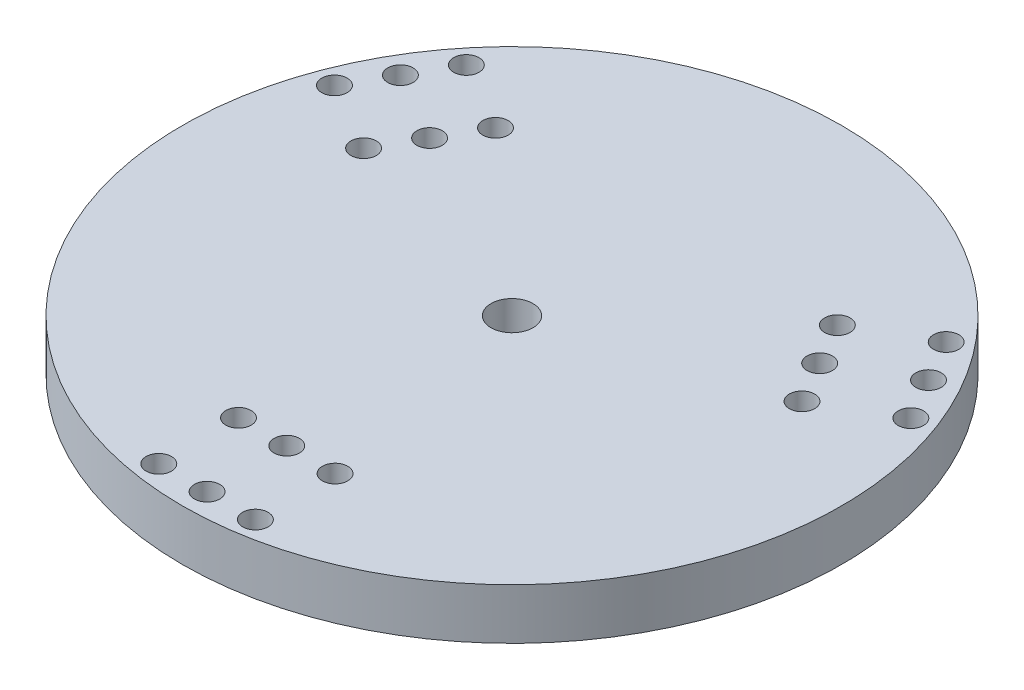
SolidWorks part; units mm, degrees
material "Carbon Fiber"
ref_plane "Front Plane" through (0, 0, 0) normal (0, 0, 1) x (1, 0, 0)
ref_plane "Top Plane" through (0, 0, 0) normal (0, 1, 0) x (1, 0, 0)
ref_plane "Right Plane" through (0, 0, 0) normal (1, 0, 0) x (0, 0, -1)
ref_plane "Plane1" through (0, 75, 0) normal (0, 1, 0) x (1, 0, 0)
sketch "Sketch1" plane through (0, 0, 0) normal (0, 1, 0) x (1, 0, 0)
  line L0 (0, 0) -> (0, -67.5) construction
  line L1 (67.5, 0) -> (-67.5, 0) construction
  line L2 (-57.6208, 33.2674) -> (-48.9649, 48.2597)
  line L3 (0, 0) -> (58.4567, 33.75) construction
  line L4 (0, 0) -> (-58.4567, 33.75) construction
  line L5 (-48.9649, 48.2597) -> (-66.2766, 18.2751)
  line L6 (-55.1208, 37.5975) -> (-60.1208, 28.9372)
  line L7 (-60.1208, 28.9372) -> (-41.6363, 18.2652)
  line L8 (0, -66.5347) -> (-17.3116, -66.5347)
  line L9 (-17.3116, -66.5347) -> (17.3116, -66.5347)
  line L10 (-41.6363, 18.2652) -> (-36.6363, 26.9255)
  line L11 (-60.1208, 28.9372) -> (-60.7961, 29.3272)
  line L12 (-55.1208, 37.5975) -> (-36.6363, 26.9255)
  line L13 (-52.6208, 41.9276) -> (-53.906, 42.6697)
  line L14 (-62.6208, 24.6071) -> (-63.906, 25.3492)
  line L15 (-52.6208, 41.9276) -> (-29.8062, 28.7556) construction
  line L16 (-39.8062, 11.4351) -> (-29.8062, 28.7556) construction
  line L17 (-62.6208, 24.6071) -> (-39.8062, 11.4351) construction
  line L18 (57.6208, 33.2674) -> (66.2766, 18.2751)
  line L19 (66.2766, 18.2751) -> (48.9649, 48.2597)
  line L20 (60.1208, 28.9372) -> (55.1208, 37.5975)
  line L21 (55.1208, 37.5975) -> (36.6363, 26.9255)
  line L22 (36.6363, 26.9255) -> (41.6363, 18.2652)
  line L23 (55.1208, 37.5975) -> (55.7961, 37.9874)
  line L24 (60.1208, 28.9372) -> (41.6363, 18.2652)
  line L25 (62.6208, 24.6071) -> (63.906, 25.3492)
  line L26 (-5, -66.5347) -> (5, -66.5347)
  line L27 (5, -66.5347) -> (5, -45.1907)
  line L28 (5, -45.1907) -> (-5, -45.1907)
  line L29 (5, -66.5347) -> (5, -67.3146)
  line L30 (-5, -66.5347) -> (-5, -45.1907)
  line L32 (52.6208, 41.9276) -> (53.906, 42.6697)
  line L33 (62.6208, 24.6071) -> (39.8062, 11.4351) construction
  line L34 (29.8062, 28.7556) -> (39.8062, 11.4351) construction
  line L35 (52.6208, 41.9276) -> (29.8062, 28.7556) construction
  line L58 (-10, -66.5347) -> (-10, -40.1907) construction
  line L59 (10, -40.1907) -> (-10, -40.1907) construction
  line L60 (10, -66.5347) -> (10, -40.1907) construction
  line L61 (-10, -66.5347) -> (-10, -68.0188)
  line L62 (10, -66.5347) -> (10, -68.0188)
  line L63 (10, -66.5347) -> (10, -67.3146) construction
  circle A0 centre (0, 0) radius 67.5
  circle A1 centre (0, 0) radius 68.75
  circle A2 centre (0, 0) radius 69.5
  circle A4 centre (0, 0) radius 5.08
  circle A5 centre (0, 0) radius 11.1125
  point P14 (0, 0)
  point P26 (-39.1363, 22.5954)
  point P39 (0, -45.1907)
  point P51 (39.1363, 22.5954)
  point P58 (0, 0)
  point P67 (0, 0)
  point P68 (0, 0)
  point P71 (0, 0)
  point P81 (0, 0)
  dimension "D1" = 135
  dimension "D2" = 137.5
  dimension "D3" = 35
  dimension "D5" = 30
  dimension "D11" = 10.16
  dimension "D12" = 22.225
  dimension "D8" = 3
  dimension "D9" = 2
  dimension "D10" = 22.3093
  dimension "D4" = 30
  dimension "D7" = 5
  dimension "D6" = 5
sketch "Sketch16" plane through (0, 75, 0) normal (0, -1, 0) x (1, 0, 0)
  line L0 (-33.6322, -30.3872) -> (-43.1322, -13.9328)
  line L1 (-47.2115, -38.2272) -> (-56.7115, -21.7728)
  line L2 (-9.5, 60) -> (9.5, 60)
  line L3 (-9.5, 44.32) -> (9.5, 44.32)
  line L4 (0, 67.5) -> (0, 0) construction
  line L5 (-67.5, 0) -> (67.5, 0) construction
  line L11 (56.7115, -21.7728) -> (47.2115, -38.2272)
  line L13 (43.1322, -13.9328) -> (33.6322, -30.3872)
  line L14 (0, 0) -> (58.4567, -33.75) construction
  line L15 (0, 0) -> (-58.4567, -33.75) construction
  circle A2 centre (0, 0) radius 68.75
  circle A3 centre (0, 0) radius 67.5
  circle A4 centre (38.3822, -22.16) radius 2.5
  circle A5 centre (51.9615, -30) radius 2.5
  circle A6 centre (-43.1322, -13.9328) radius 2.5
  circle A7 centre (-38.3822, -22.16) radius 2.5
  circle A8 centre (-51.9615, -30) radius 2.5
  circle A9 centre (0, 44.32) radius 2.5
  circle A10 centre (0, 60) radius 2.5
  circle A11 centre (-33.6322, -30.3872) radius 2.5
  circle A12 centre (-47.2115, -38.2272) radius 2.5
  circle A13 centre (-56.7115, -21.7728) radius 2.5
  circle A14 centre (9.5, 44.32) radius 2.5
  circle A15 centre (-9.5, 44.32) radius 2.5
  circle A16 centre (-9.5, 60) radius 2.5
  circle A17 centre (9.5, 60) radius 2.5
  circle A18 centre (33.6322, -30.3872) radius 2.5
  circle A19 centre (43.1322, -13.9328) radius 2.5
  circle A20 centre (56.7115, -21.7728) radius 2.5
  circle A21 centre (47.2115, -38.2272) radius 2.5
  circle A22 centre (0, 0) radius 64.85
  circle A23 centre (0, 0) radius 4.1275
  point P23 (0, 0)
  point P24 (-38.3822, -22.16)
  point P27 (-51.9615, -30)
  point P31 (0, 44.32)
  dimension "D4" = 15.68
  dimension "D5" = 7.5
  dimension "D1" = 137.5
  dimension "D2" = 135
  dimension "D3" = 5
  dimension "D8" = 5
  dimension "D10" = 129.7
  dimension "D11" = 8.255
  dimension "D7" = 19
  dimension "D6" = 3
  dimension "D9" = 3
extrude "Boss-Extrude1" add sketch "Sketch16" along normal blind 10
